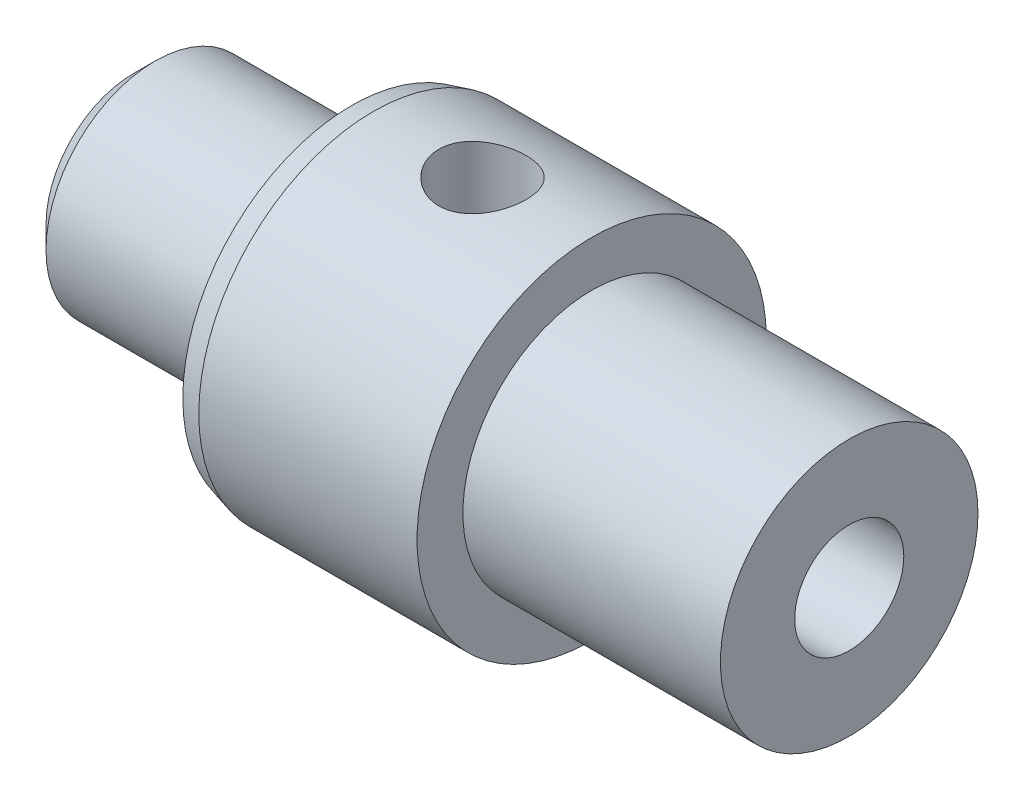
SolidWorks part; units mm, degrees
ref_plane "Front Plane" through (0, 0, 0) normal (0, 0, 1) x (1, 0, 0)
ref_plane "Top Plane" through (0, 0, 0) normal (0, 1, 0) x (1, 0, 0)
ref_plane "Right Plane" through (0, 0, 0) normal (1, 0, 0) x (0, 0, -1)
sketch "Sketch1" plane through (0, 0, 0) normal (0, 0, 1) x (1, 0, 0)
  line L0 (5, 4) -> (5, 0)
  line L1 (5, 0) -> (10.5, 0)
  line L2 (10.5, 0) -> (10.5, 4)
  line L3 (10.5, 4) -> (5, 4)
  line L4 (5, 0) -> (10.5, 0) construction
revolve "Revolve1" add sketch "Sketch1" angle 360 about L4
sketch "Sketch2" plane through (5, 0, 0) normal (-1, 0, 0) x (0, 0, 1)
  circle A0 centre (0, 0) radius 2.5
extrude "Boss-Extrude1" add sketch "Sketch2" along normal blind 5
sketch "Sketch3" plane through (10.5, 0, 0) normal (1, 0, 0) x (0, 0, -1)
  circle A0 centre (0, 0) radius 2.95
extrude "Boss-Extrude2" add sketch "Sketch3" along normal blind 5.9
hole_wizard "Ø2.0 (2) Diameter Hole1" positions "3DSketch1" profile "Sketch4" hole size "Ø2.0" standard "ANSI Metric"
sketch3d "3DSketch1"
  point P0 (8, -4, 0)
sketch "Sketch4" plane through (8, -4, 0) normal (1, 0, 0) x (0, 0, -1)
  line L0 (0, 0) -> (0, 8)
  line L1 (0, 8) -> (1, 8)
  line L2 (1, 8) -> (1, 0)
  line L5 (1, 0) -> (0, 0)
  line L11 (0, -6.35) -> (0, 107.95) construction
  dimension "Thru Hole Dia." = 2
  dimension "Thru Hole Depth" = 8
hole_wizard "Tap Drill for M3x0.5 Tap1" positions "Sketch6" profile "Sketch5" hole size "M3x0.5" standard "ANSI Metric"
sketch "Sketch6" plane through (16.4, 0, 0) normal (1, 0, 0) x (0, 0, -1)
  point P0 (0, 0)
sketch "Sketch5" plane through (16.4, 0, 0) normal (0, 1, 0) x (0, 0, -1)
  line L0 (0, 0) -> (0, 6.7511)
  line L1 (0, 6.7511) -> (1.25, 6)
  line L2 (1.25, 6) -> (1.25, 0)
  line L5 (1.25, 0) -> (0, 0)
  line L10 (0, 6.7511) -> (-1.25, 6) construction
  line L11 (0, -6.35) -> (0, 107.95) construction
  dimension "Hole Dia." = 2.5
  dimension "Hole Depth" = 6
  dimension "Drill Angle" = 118
chamfer "Chamfer1" distance 0.5 angle 45 1 edges at (0, 0, 2.5)
chamfer "Chamfer2" distance 0.134 angle 75 1 edges at (5, 0, -4)
